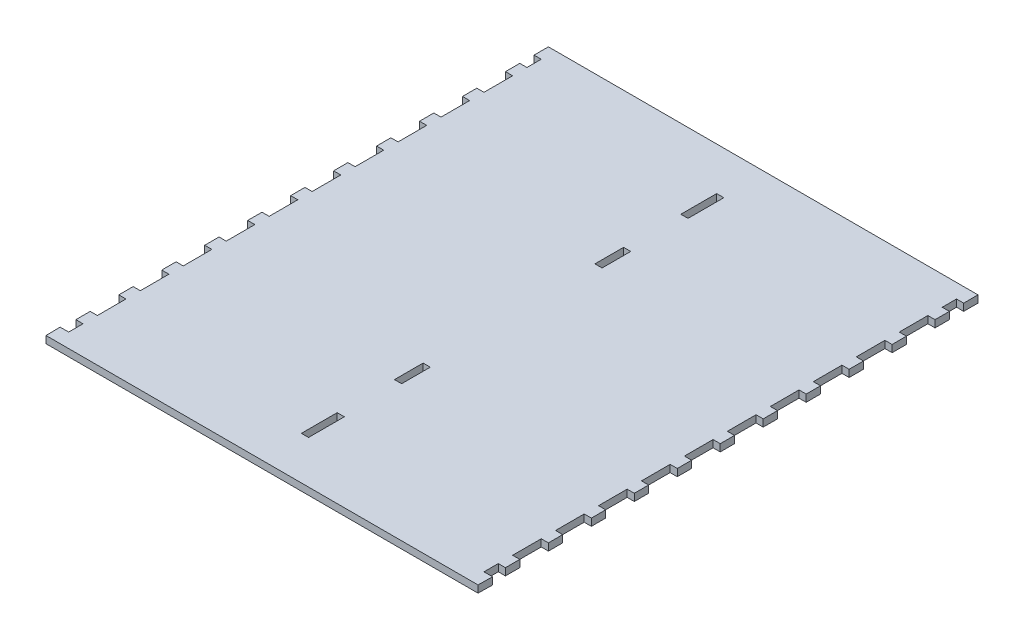
SolidWorks part; units mm, degrees
ref_plane "Front Plane" through (0, 0, 0) normal (0, 0, 1) x (1, 0, 0)
ref_plane "Top Plane" through (0, 0, 0) normal (0, 1, 0) x (1, 0, 0)
ref_plane "Right Plane" through (0, 0, 0) normal (1, 0, 0) x (0, 0, -1)
sketch "Sketch1" plane through (0, 0, 0) normal (0, 1, 0) x (1, 0, 0)
  line L0 (-24.83, 345.545) -> (-19.83, 345.545)
  line L1 (-24.83, 355.545) -> (275.17, 355.545)
  line L2 (-24.83, 355.545) -> (-24.83, 345.545)
  line L3 (-25.677, 5.546) -> (276.017, 5.546)
  line L4 (-19.83, 345.545) -> (-19.83, 335.545)
  line L5 (-25.8201, 15.545) -> (-25.677, 5.546)
  line L6 (-19.83, 335.545) -> (-24.83, 335.545)
  line L7 (-24.83, 335.545) -> (-24.83, 325.545)
  line L8 (-24.83, 325.545) -> (-19.83, 325.545)
  line L9 (-19.83, 325.545) -> (-19.83, 315.545)
  line L10 (-19.83, 315.545) -> (-19.83, 305.545)
  line L11 (-19.83, 305.545) -> (-24.83, 305.545)
  line L12 (-24.83, 305.545) -> (-24.83, 295.545)
  line L13 (-24.83, 295.545) -> (-19.83, 295.545)
  line L14 (-19.83, 295.545) -> (-19.83, 285.545)
  line L15 (-19.83, 285.545) -> (-19.83, 275.545)
  line L16 (-19.83, 275.545) -> (-24.83, 275.545)
  line L17 (-24.83, 275.545) -> (-24.83, 265.545)
  line L18 (-24.83, 265.545) -> (-19.83, 265.545)
  line L19 (-19.83, 265.545) -> (-19.83, 255.545)
  line L20 (-19.83, 255.545) -> (-19.83, 245.545)
  line L21 (-19.83, 245.545) -> (-24.83, 245.545)
  line L22 (-24.83, 245.545) -> (-24.83, 235.545)
  line L23 (-24.83, 235.545) -> (-19.83, 235.545)
  line L24 (-19.83, 235.545) -> (-19.83, 225.545)
  line L25 (-19.83, 225.545) -> (-19.83, 215.545)
  line L26 (-19.83, 215.545) -> (-24.83, 215.545)
  line L27 (-24.83, 215.545) -> (-24.83, 205.545)
  line L28 (-24.83, 205.545) -> (-19.83, 205.545)
  line L29 (-19.83, 205.545) -> (-19.83, 195.545)
  line L30 (-19.83, 195.545) -> (-19.83, 185.545)
  line L31 (-19.83, 185.545) -> (-24.83, 185.545)
  line L32 (-24.83, 185.545) -> (-24.83, 175.545)
  line L33 (-24.83, 175.545) -> (-19.83, 175.545)
  line L34 (-19.83, 175.545) -> (-19.83, 165.545)
  line L35 (-19.83, 165.545) -> (-19.83, 155.545)
  line L36 (-19.83, 155.545) -> (-24.83, 155.545)
  line L37 (-24.83, 155.545) -> (-24.83, 145.545)
  line L38 (-24.83, 145.545) -> (-19.83, 145.545)
  line L39 (-19.83, 145.545) -> (-19.83, 135.545)
  line L40 (-19.83, 135.545) -> (-19.83, 125.545)
  line L41 (-19.83, 125.545) -> (-24.83, 125.545)
  line L42 (-24.83, 125.545) -> (-24.83, 115.545)
  line L43 (-24.83, 115.545) -> (-19.83, 115.545)
  line L44 (-19.83, 115.545) -> (-19.83, 105.545)
  line L45 (-19.83, 105.545) -> (-19.83, 95.545)
  line L46 (-19.83, 95.545) -> (-24.83, 95.545)
  line L47 (-24.83, 95.545) -> (-24.83, 85.545)
  line L48 (-24.83, 85.545) -> (-19.83, 85.545)
  line L49 (-19.83, 85.545) -> (-19.83, 75.545)
  line L50 (-19.83, 75.545) -> (-19.83, 65.545)
  line L51 (-19.83, 65.545) -> (-24.83, 65.545)
  line L52 (-24.83, 65.545) -> (-24.83, 55.545)
  line L53 (-24.83, 55.545) -> (-19.83, 55.545)
  line L54 (-19.83, 55.545) -> (-19.83, 45.545)
  line L55 (-19.83, 45.545) -> (-19.83, 35.545)
  line L56 (-19.83, 35.545) -> (-24.83, 35.545)
  line L57 (-24.83, 35.545) -> (-24.83, 25.545)
  line L58 (-24.83, 25.545) -> (-19.83, 25.545)
  line L59 (-19.83, 25.545) -> (-19.83, 15.545)
  line L60 (-19.83, 15.545) -> (-25.8201, 15.545)
  line L61 (125.17, 5.546) -> (125.17, 355.545) construction
  line L62 (270.17, 15.545) -> (276.1602, 15.545)
  line L63 (270.17, 25.545) -> (270.17, 15.545)
  line L64 (275.17, 25.545) -> (270.17, 25.545)
  line L65 (275.17, 35.545) -> (275.17, 25.545)
  line L66 (270.17, 35.545) -> (275.17, 35.545)
  line L67 (270.17, 45.545) -> (270.17, 35.545)
  line L68 (270.17, 55.545) -> (270.17, 45.545)
  line L69 (275.17, 55.545) -> (270.17, 55.545)
  line L70 (275.17, 65.545) -> (275.17, 55.545)
  line L71 (270.17, 65.545) -> (275.17, 65.545)
  line L72 (270.17, 75.545) -> (270.17, 65.545)
  line L73 (270.17, 85.545) -> (270.17, 75.545)
  line L74 (275.17, 85.545) -> (270.17, 85.545)
  line L75 (275.17, 95.545) -> (275.17, 85.545)
  line L76 (270.17, 95.545) -> (275.17, 95.545)
  line L77 (270.17, 105.545) -> (270.17, 95.545)
  line L78 (270.17, 115.545) -> (270.17, 105.545)
  line L79 (275.17, 115.545) -> (270.17, 115.545)
  line L80 (275.17, 125.545) -> (275.17, 115.545)
  line L81 (270.17, 125.545) -> (275.17, 125.545)
  line L82 (270.17, 135.545) -> (270.17, 125.545)
  line L83 (270.17, 145.545) -> (270.17, 135.545)
  line L84 (275.17, 145.545) -> (270.17, 145.545)
  line L85 (275.17, 155.545) -> (275.17, 145.545)
  line L86 (270.17, 155.545) -> (275.17, 155.545)
  line L87 (270.17, 165.545) -> (270.17, 155.545)
  line L88 (270.17, 175.545) -> (270.17, 165.545)
  line L89 (275.17, 175.545) -> (270.17, 175.545)
  line L90 (275.17, 185.545) -> (275.17, 175.545)
  line L91 (270.17, 185.545) -> (275.17, 185.545)
  line L92 (270.17, 195.545) -> (270.17, 185.545)
  line L93 (270.17, 205.545) -> (270.17, 195.545)
  line L94 (275.17, 205.545) -> (270.17, 205.545)
  line L95 (275.17, 215.545) -> (275.17, 205.545)
  line L96 (270.17, 215.545) -> (275.17, 215.545)
  line L97 (270.17, 225.545) -> (270.17, 215.545)
  line L98 (270.17, 235.545) -> (270.17, 225.545)
  line L99 (275.17, 235.545) -> (270.17, 235.545)
  line L100 (275.17, 245.545) -> (275.17, 235.545)
  line L101 (270.17, 245.545) -> (275.17, 245.545)
  line L102 (270.17, 255.545) -> (270.17, 245.545)
  line L103 (270.17, 265.545) -> (270.17, 255.545)
  line L104 (275.17, 265.545) -> (270.17, 265.545)
  line L105 (275.17, 275.545) -> (275.17, 265.545)
  line L106 (270.17, 275.545) -> (275.17, 275.545)
  line L107 (270.17, 285.545) -> (270.17, 275.545)
  line L108 (270.17, 295.545) -> (270.17, 285.545)
  line L109 (275.17, 295.545) -> (270.17, 295.545)
  line L110 (275.17, 305.545) -> (275.17, 295.545)
  line L111 (270.17, 305.545) -> (275.17, 305.545)
  line L112 (270.17, 315.545) -> (270.17, 305.545)
  line L113 (270.17, 325.545) -> (270.17, 315.545)
  line L114 (275.17, 325.545) -> (270.17, 325.545)
  line L115 (275.17, 335.545) -> (275.17, 325.545)
  line L116 (270.17, 335.545) -> (275.17, 335.545)
  line L117 (276.1602, 15.545) -> (276.017, 5.546)
  line L118 (270.17, 345.545) -> (270.17, 335.545)
  line L119 (275.17, 355.545) -> (275.17, 345.545)
  line L120 (275.17, 345.545) -> (270.17, 345.545)
  line L122 (122.67, 325.545) -> (127.67, 325.545)
  line L123 (122.67, 325.545) -> (122.67, 300.545)
  line L124 (122.67, 300.545) -> (127.67, 300.545)
  line L125 (127.67, 325.545) -> (127.67, 300.545)
  line L126 (122.67, 325.545) -> (127.67, 300.545) construction
  line L127 (122.67, 300.545) -> (127.67, 325.545) construction
  line L128 (122.67, 60.546) -> (127.67, 60.546)
  line L129 (122.67, 60.546) -> (122.67, 35.546)
  line L130 (122.67, 35.546) -> (127.67, 35.546)
  line L131 (127.67, 60.546) -> (127.67, 35.546)
  line L132 (122.67, 60.546) -> (127.67, 35.546) construction
  line L133 (122.67, 35.546) -> (127.67, 60.546) construction
  line L134 (122.67, 260.545) -> (127.67, 260.545)
  line L135 (122.67, 260.545) -> (122.67, 240.545)
  line L136 (122.67, 240.545) -> (127.67, 240.545)
  line L137 (127.67, 260.545) -> (127.67, 240.545)
  line L138 (122.67, 260.545) -> (127.67, 240.545) construction
  line L139 (122.67, 240.545) -> (127.67, 260.545) construction
  line L140 (122.67, 100.546) -> (127.67, 100.546)
  line L141 (122.67, 100.546) -> (122.67, 120.546)
  line L142 (122.67, 120.546) -> (127.67, 120.546)
  line L143 (127.67, 100.546) -> (127.67, 120.546)
  line L144 (122.67, 100.546) -> (127.67, 120.546) construction
  line L145 (122.67, 120.546) -> (127.67, 100.546) construction
  point P122 (125.17, 313.045)
  point P127 (125.17, 48.046)
  point P132 (125.17, 250.545)
  point P137 (125.17, 110.546)
  dimension "D1" = 350
  dimension "D2" = 5
  dimension "ShelfWidth" = 300
  dimension "D3" = 10
  dimension "D4" = 5
  dimension "D5" = 10
  dimension "D7" = 30
  dimension "D8" = 25
  dimension "D9" = 30
  dimension "D10" = 20
  dimension "D11" = 40
  dimension "D12" = 40
  dimension "D6" = 11
extrude "Boss-Extrude2" add sketch "Sketch1" along normal blind 5
